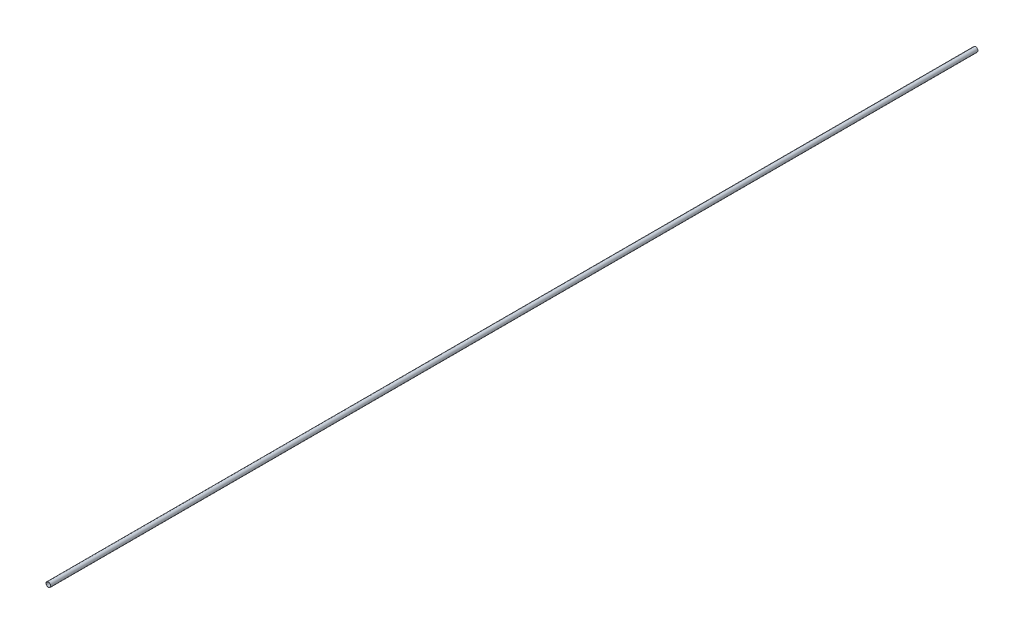
SolidWorks part; units mm, degrees
ref_plane "Front Plane" through (0, 0, 0) normal (0, 0, 1) x (1, 0, 0)
ref_plane "Top Plane" through (0, 0, 0) normal (0, 1, 0) x (1, 0, 0)
ref_plane "Right Plane" through (0, 0, 0) normal (1, 0, 0) x (0, 0, -1)
sketch "Sketch1" plane through (0, 0, 0) normal (0, 0, 1) x (1, 0, 0)
  circle A0 centre (2675.1058, 3025.346) radius 3.8862
  circle A1 centre (2675.1058, 3025.346) radius 3.5306
extrude "Boss-Extrude1" add sketch "Sketch1" along normal blind 1524
